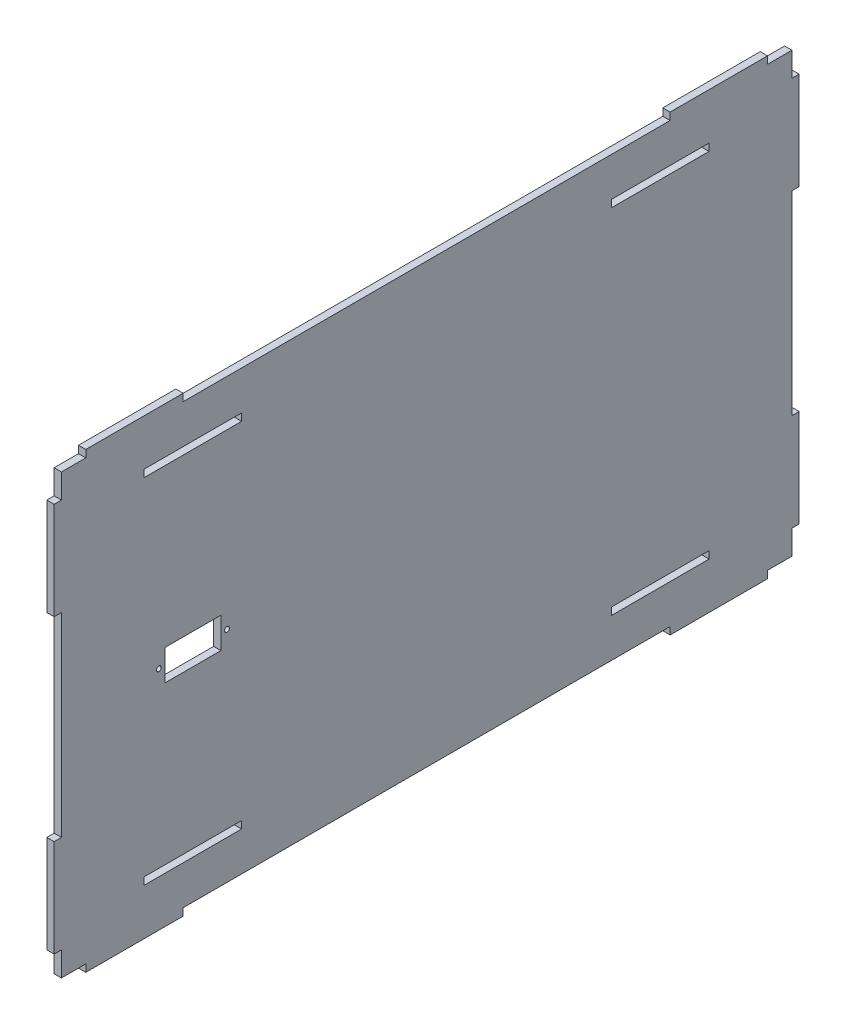
SolidWorks part; units mm, degrees
ref_plane "Front Plane" through (0, 0, 0) normal (0, 0, 1) x (1, 0, 0)
ref_plane "Top Plane" through (0, 0, 0) normal (0, 1, 0) x (1, 0, 0)
ref_plane "Right Plane" through (0, 0, 0) normal (1, 0, 0) x (0, 0, -1)
sketch "Sketch1" plane through (0, 0, 0) normal (1, 0, 0) x (0, 0, -1)
  line L1 (0, 0) -> (-300, 0)
  line L2 (0, 0) -> (0, 180)
  line L3 (0, 180) -> (-300, 180)
  line L4 (-300, 0) -> (-300, 180)
  dimension "D1" = 300
  dimension "D2" = 180
extrude "Boss-Extrude1" add sketch "Sketch1" along normal blind 3
sketch "Sketch2" plane through (3, 0, 0) normal (1, 0, 0) x (0, 0, -1)
  line L0 (0, 180) -> (-300, 180) construction
  line L1 (-290, 180) -> (-250, 180)
  line L2 (-290, 180) -> (-290, 183)
  line L3 (-290, 183) -> (-250, 183)
  line L4 (-250, 180) -> (-250, 183)
  line L5 (0, 0) -> (0, 180) construction
  line L6 (-50, 180) -> (-10, 180)
  line L7 (-50, 180) -> (-50, 183)
  line L8 (-50, 183) -> (-10, 183)
  line L9 (-10, 180) -> (-10, 183)
  line L10 (0, 170) -> (3, 170)
  line L11 (0, 170) -> (0, 130)
  line L12 (0, 130) -> (3, 130)
  line L13 (3, 170) -> (3, 130)
  line L14 (-300, 0) -> (0, 0) construction
  line L15 (0, 50) -> (3, 50)
  line L16 (0, 50) -> (0, 10)
  line L17 (0, 10) -> (3, 10)
  line L18 (3, 50) -> (3, 10)
  line L19 (-10, 0) -> (-50, 0)
  line L20 (-10, 0) -> (-10, -3)
  line L21 (-10, -3) -> (-50, -3)
  line L22 (-50, 0) -> (-50, -3)
  line L23 (-300, 180) -> (-300, 0) construction
  line L24 (-290, 0) -> (-250, 0)
  line L25 (-290, 0) -> (-290, -3)
  line L26 (-290, -3) -> (-250, -3)
  line L27 (-250, 0) -> (-250, -3)
  line L28 (-300, 170) -> (-303, 170)
  line L29 (-300, 170) -> (-300, 130)
  line L30 (-300, 130) -> (-303, 130)
  line L31 (-303, 170) -> (-303, 130)
  line L33 (-300, 50) -> (-303, 50)
  line L34 (-300, 50) -> (-300, 10)
  line L35 (-300, 10) -> (-303, 10)
  line L36 (-303, 50) -> (-303, 10)
  dimension "D1" = 3
  dimension "D2" = 40
  dimension "D3" = 40
  dimension "D4" = 40
  dimension "D5" = 3
  dimension "D6" = 10
  dimension "D7" = 10
  dimension "D8" = 10
  dimension "D9" = 10
extrude "Boss-Extrude2" add sketch "Sketch2" against normal blind 3
sketch "Sketch3" plane through (3, 0, 0) normal (1, 0, 0) x (0, 0, -1)
  line L0 (-250, 183) -> (-290, 183) construction
  line L1 (-290, -3) -> (-250, -3) construction
  line L2 (-266, 19) -> (-226, 19)
  line L3 (-266, 164) -> (-226, 164)
  line L4 (-266, 19) -> (-266, 16)
  line L5 (-266, 164) -> (-226, 164)
  line L6 (-266, 164) -> (-266, 161)
  line L7 (-266, 161) -> (-226, 161)
  line L8 (-226, 164) -> (-226, 161)
  line L9 (-266, 16) -> (-226, 16)
  line L10 (-226, 19) -> (-226, 16)
  line L11 (-10, 183) -> (-50, 183) construction
  line L12 (-77, 164) -> (-37, 164)
  line L13 (-77, 164) -> (-77, 161)
  line L14 (-77, 161) -> (-37, 161)
  line L15 (-37, 164) -> (-37, 161)
  line L16 (0, 0) -> (0, 10) construction
  line L17 (-77, 19) -> (-37, 19)
  line L18 (-77, 19) -> (-77, 16)
  line L19 (-77, 16) -> (-37, 16)
  line L20 (-37, 19) -> (-37, 16)
  line L21 (-50, -3) -> (-10, -3) construction
  dimension "D1" = 19
  dimension "D2" = 19
  dimension "D3" = 3
  dimension "D4" = 40
  dimension "D5" = 3
  dimension "D6" = 40
  dimension "D7" = 19
  dimension "D8" = 37
  dimension "D9" = 37
  dimension "D10" = 40
  dimension "D11" = 3
  dimension "D12" = 37
  dimension "D13" = 19
extrude "Cut-Extrude1" cut sketch "Sketch3" against normal through all contours L6 L7 L8 L5
sketch "Sketch4" plane through (3, 0, 0) normal (1, 0, 0) x (0, 0, -1)
  line L1 (-74, 164) -> (-34, 164)
  line L2 (-74, 164) -> (-74, 161)
  line L3 (-74, 161) -> (-34, 161)
  line L4 (-34, 164) -> (-34, 161)
  dimension "D1" = 37
  dimension "D2" = 19
  dimension "D3" = 40
  dimension "D4" = 3
extrude "Cut-Extrude2" cut sketch "Sketch4" against normal blind 3
sketch "Sketch5" plane through (3, 0, 0) normal (1, 0, 0) x (0, 0, -1)
  line L3 (-266, 19) -> (-226, 19)
  line L4 (-266, 19) -> (-266, 16)
  line L5 (-266, 16) -> (-226, 16)
  line L6 (-226, 19) -> (-226, 16)
  dimension "D1" = 37
  dimension "D2" = 19
  dimension "D3" = 3
  dimension "D4" = 40
extrude "Cut-Extrude3" cut sketch "Sketch5" against normal blind 3
sketch "Sketch6" plane through (3, 0, 0) normal (1, 0, 0) x (0, 0, -1)
  line L1 (-74, 19) -> (-34, 19)
  line L2 (-74, 19) -> (-74, 16)
  line L3 (-74, 16) -> (-34, 16)
  line L4 (-34, 19) -> (-34, 16)
  dimension "D1" = 19
  dimension "D2" = 37
  dimension "D3" = 40
  dimension "D4" = 3
extrude "Cut-Extrude4" cut sketch "Sketch6" against normal blind 3
sketch "Sketch8" plane through (3, 0, 0) normal (1, 0, 0) x (0, 0, -1)
  line L0 (-266, 161) -> (-226, 161) construction
  line L1 (-257.515, 96.295) -> (-234.485, 96.295)
  line L2 (-257.515, 96.295) -> (-257.515, 83.705)
  line L3 (-257.515, 83.705) -> (-234.485, 83.705)
  line L4 (-234.485, 96.295) -> (-234.485, 83.705)
  line L6 (-300, 130) -> (-300, 50) construction
  point P4 (-300, 90)
  point P6 (-257.515, 90)
  point P9 (-246, 161)
  point P11 (-246, 96.295)
  dimension "D1" = 12.59
  dimension "D2" = 23.03
extrude "Cut-Extrude5" cut sketch "Sketch8" against normal blind 10
sketch "Sketch9" plane through (3, 0, 0) normal (1, 0, 0) x (0, 0, -1)
  line L0 (-257.515, 96.295) -> (-257.515, 83.705) construction
  line L1 (-234.485, 83.705) -> (-234.485, 96.295) construction
  circle A0 centre (-260.015, 90) radius 1
  circle A1 centre (-231.985, 90) radius 1
  point P6 (-257.515, 90)
  point P11 (-234.485, 90)
  dimension "D1" = 2
  dimension "D2" = 2.5
  dimension "D3" = 2.5
extrude "Cut-Extrude6" cut sketch "Sketch9" against normal blind 2
sketch "Sketch12" plane through (1, 0, 0) normal (1, 0, 0) x (0, 0, -1)
  circle A0 centre (-260.015, 90) radius 1.5
  circle A1 centre (-260.015, 90) radius 1 construction
  dimension "D1" = 3
extrude "Cut-Extrude7" cut sketch "Sketch12" against normal blind 10
sketch "Sketch13" plane through (1, 0, 0) normal (1, 0, 0) x (0, 0, -1)
  circle A0 centre (-231.985, 90) radius 1.5
  circle A1 centre (-231.985, 90) radius 1 construction
  dimension "D1" = 3
extrude "Cut-Extrude8" cut sketch "Sketch13" against normal blind 10
